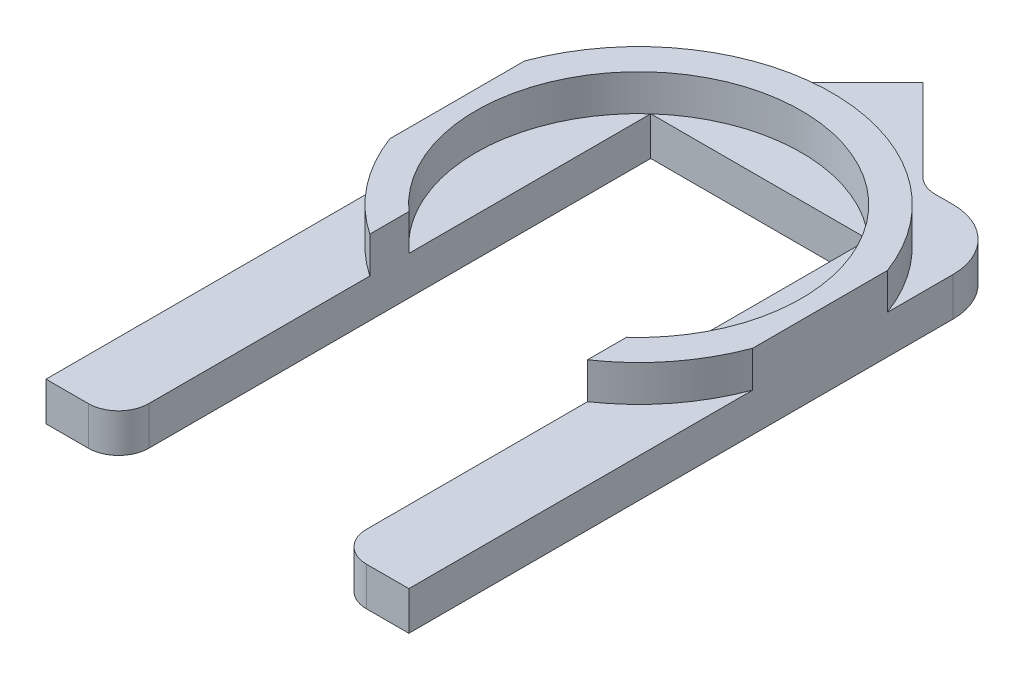
SolidWorks part; units mm, degrees
ref_plane "Front" through (0, 0, 0) normal (0, 0, 1) x (1, 0, 0)
ref_plane "Top" through (0, 0, 0) normal (0, 1, 0) x (1, 0, 0)
ref_plane "Right" through (0, 0, 0) normal (1, 0, 0) x (0, 0, -1)
sketch "Sketch1" plane through (0, 0, 0) normal (0, 1, 0) x (1, 0, 0)
  line L0 (-15, -25) -> (-9, -25)
  line L2 (15, -25) -> (15, 25)
  line L3 (15, 25) -> (7.5, 25)
  line L4 (-15, -25) -> (-15, 25)
  line L5 (15, -25) -> (-15, 25) construction
  line L6 (15, 25) -> (-15, -25) construction
  line L7 (9, -25) -> (15, -25)
  line L9 (-9, -25) -> (-9, 19)
  line L10 (9, -25) -> (9, 19)
  line L11 (-9, 19) -> (9, 19)
  line L13 (0, 32.5) -> (7.5, 25)
  line L15 (0, 32.5) -> (-7.5, 25)
  line L17 (-7.5, 25) -> (-15, 25)
  point P0 (0, 0)
extrude "Boss-Extrude1" add sketch "Sketch1" along normal blind 3.2
sketch "Sketch2" plane through (0, 3.2, 0) normal (0, 1, 0) x (1, 0, 0)
  line L0 (-9, -4.2288) -> (-9, -1)
  line L2 (-15, 14.5678) -> (-15, 3.4322)
  line L4 (15, 14.5678) -> (15, 3.4322)
  line L9 (9, -1) -> (9, -4.2288)
  arc A0 (9, -1) -> (-9, -1) centre (0, 9) ccw
  arc A1 (-15, 3.4322) -> (-9, -4.2288) centre (0, 9) ccw
  arc A2 (15, 14.5678) -> (-15, 14.5678) centre (0, 9) ccw
  arc A3 (9, -4.2288) -> (15, 3.4322) centre (0, 9) ccw
extrude "Boss-Extrude2" add sketch "Sketch2" along normal blind 3
fillet "Fillet1" radius 5 2 edges at (15, 1.6, -25) (-15, 1.6, -25)
fillet "Fillet2" radius 2.5 4 edges at (9, 1.6, 25) (-9, 1.6, 25) (7.5, 1.6, -25) (-7.5, 1.6, -25)
